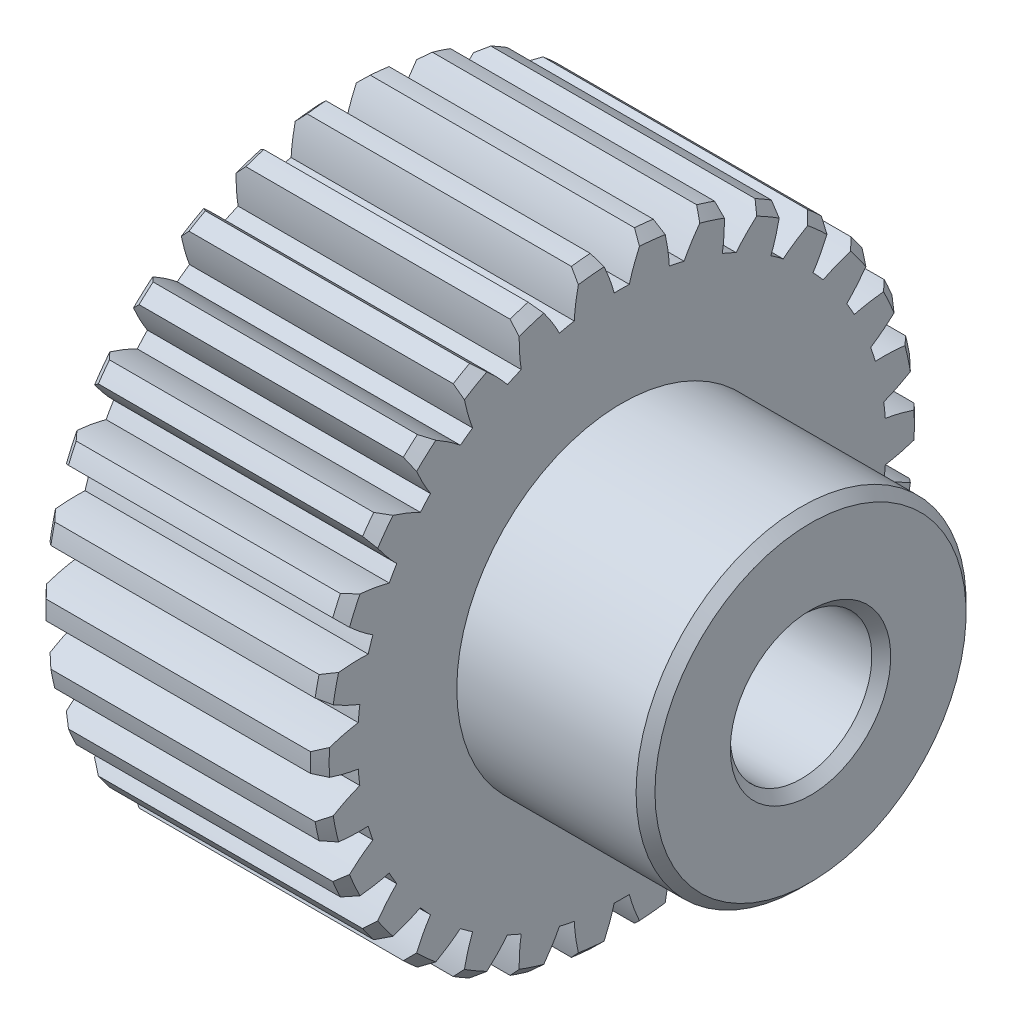
SolidWorks part; units mm, degrees
ref_plane "Ön Düzlem" through (0, 0, 0) normal (0, 0, 1) x (1, 0, 0)
ref_plane "Üst Düzlem" through (0, 0, 0) normal (0, 1, 0) x (1, 0, 0)
ref_plane "Sağ Düzlem" through (0, 0, 0) normal (1, 0, 0) x (0, 0, -1)
sketch "Sketch1" plane through (0, 0, 0) normal (0, 0, 1) x (1, 0, 0)
  line L0 (-35.4302, 0) -> (66.3715, 0) construction
  line L1 (-12.0238, 16) -> (2.9762, 16)
  line L2 (-11.5238, 3.75) -> (12.4762, 3.75)
  line L3 (-12.0238, 16) -> (-12.0238, 4.25)
  line L4 (2.9762, 16) -> (2.9762, 8.7418)
  line L5 (2.9762, 8.7418) -> (12.4762, 8.7418)
  line L6 (12.9762, 8.2418) -> (12.9762, 4.25)
  line L7 (-12.0238, 4.25) -> (-11.5238, 3.75)
  line L8 (12.4762, 3.75) -> (12.9762, 4.25)
  line L9 (12.4762, 8.7418) -> (12.9762, 8.2418)
  point P5 (-12.0238, 3.75)
  point P6 (12.9762, 3.75)
  point P9 (12.9762, 8.7418)
  dimension "D1" = 16
  dimension "D2" = 15
  dimension "D3" = 3.75
  dimension "D4" = 25
revolve "Revolve1" add sketch "Sketch1" angle 360 about L0
sketch "Sketch2" plane through (-12.0238, 0, 0) normal (-1, 0, 0) x (0, 0, 1)
  line L0 (0, 0) -> (0, 20.4654) construction
  line L1 (0, 0) -> (2.1392, 20.3533) construction
  line L2 (0, 0) -> (4.255, 20.0182) construction
  line L3 (0, 0) -> (6.3242, 19.4638) construction
  line L4 (0, 0) -> (8.324, 18.6961) construction
  line L5 (0, 0) -> (10.2327, 17.7236) construction
  line L6 (0, 0) -> (12.0293, 16.5569) construction
  line L7 (0, 0) -> (13.6941, 15.2088) construction
  line L8 (0, 0) -> (15.2088, 13.6941) construction
  line L9 (0, 0) -> (16.5569, 12.0293) construction
  line L10 (0, 0) -> (17.7236, 10.2327) construction
  line L11 (0, 0) -> (18.6961, 8.324) construction
  line L12 (0, 0) -> (19.4638, 6.3242) construction
  line L13 (0, 0) -> (20.0182, 4.255) construction
  line L14 (0, 0) -> (20.3533, 2.1392) construction
  line L15 (0, 0) -> (20.4654, 0) construction
  line L16 (0, 0) -> (20.3533, -2.1392) construction
  line L17 (0, 0) -> (20.0182, -4.255) construction
  line L18 (0, 0) -> (19.4638, -6.3242) construction
  line L19 (0, 0) -> (18.6961, -8.324) construction
  line L20 (0, 0) -> (17.7236, -10.2327) construction
  line L21 (0, 0) -> (16.5569, -12.0293) construction
  line L22 (0, 0) -> (15.2088, -13.6941) construction
  line L23 (0, 0) -> (13.6941, -15.2088) construction
  line L24 (0, 0) -> (12.0293, -16.5569) construction
  line L25 (0, 0) -> (10.2327, -17.7236) construction
  line L26 (0, 0) -> (8.324, -18.6961) construction
  line L27 (0, 0) -> (6.3242, -19.4638) construction
  line L28 (0, 0) -> (4.255, -20.0182) construction
  line L29 (0, 0) -> (2.1392, -20.3533) construction
  line L30 (0, 0) -> (0, -20.4654) construction
  line L31 (0, 0) -> (-2.1392, -20.3533) construction
  line L32 (0, 0) -> (-4.255, -20.0182) construction
  line L33 (0, 0) -> (-6.3242, -19.4638) construction
  line L34 (0, 0) -> (-8.324, -18.6961) construction
  line L35 (0, 0) -> (-10.2327, -17.7236) construction
  line L36 (0, 0) -> (-12.0293, -16.5569) construction
  line L37 (0, 0) -> (-13.6941, -15.2088) construction
  line L38 (0, 0) -> (-15.2088, -13.6941) construction
  line L39 (0, 0) -> (-16.5569, -12.0293) construction
  line L40 (0, 0) -> (-17.7236, -10.2327) construction
  line L41 (0, 0) -> (-18.6961, -8.324) construction
  line L42 (0, 0) -> (-19.4638, -6.3242) construction
  line L43 (0, 0) -> (-20.0182, -4.255) construction
  line L44 (0, 0) -> (-20.3533, -2.1392) construction
  line L45 (0, 0) -> (-20.4654, 0) construction
  line L46 (0, 0) -> (-20.3533, 2.1392) construction
  line L47 (0, 0) -> (-20.0182, 4.255) construction
  line L48 (0, 0) -> (-19.4638, 6.3242) construction
  line L49 (0, 0) -> (-18.6961, 8.324) construction
  line L50 (0, 0) -> (-17.7236, 10.2327) construction
  line L51 (0, 0) -> (-16.5569, 12.0293) construction
  line L52 (0, 0) -> (-15.2088, 13.6941) construction
  line L53 (0, 0) -> (-13.6941, 15.2088) construction
  line L54 (0, 0) -> (-12.0293, 16.5569) construction
  line L55 (0, 0) -> (-10.2327, 17.7236) construction
  line L56 (0, 0) -> (-8.324, 18.6961) construction
  line L57 (0, 0) -> (-6.3242, 19.4638) construction
  line L58 (0, 0) -> (-4.255, 20.0182) construction
  line L59 (0, 0) -> (-2.1392, 20.3533) construction
  circle A0 centre (0, 0) radius 14.0018
  circle A1 centre (0, 0) radius 16 construction
  spline S0 degree 2 poles (-1.1744, 15.9568) (-0.682, 15.0183) (-0.4, 13.9961) knots 0 0 0 1 1 1
  spline S1 degree 2 poles (1.1744, 15.9568) (0.6777, 15.02) (0.4, 13.9961) knots 0 0 0 1 1 1
  circle M62 centre (0, 0) radius 16
  dimension "D1" = 60
  dimension "D2" = 0.4
  dimension "D3" = 0.4
  dimension "D4" = 0.5
  dimension "D5" = 0.5
extrude "Cut-Extrude2" cut sketch "Sketch2" against normal blind 16 contours S1 S0 A0 M62
chamfer "Chamfer1" distance 0.5 angle 45 2 edges at (2.9762, -16, 0) (-12.0238, -16, 0)
pattern_circular "CirPattern5" count 30 over 360 about axis through (-11.5238, 0, 0) along (1, 0, 0) of "Cut-Extrude2"
